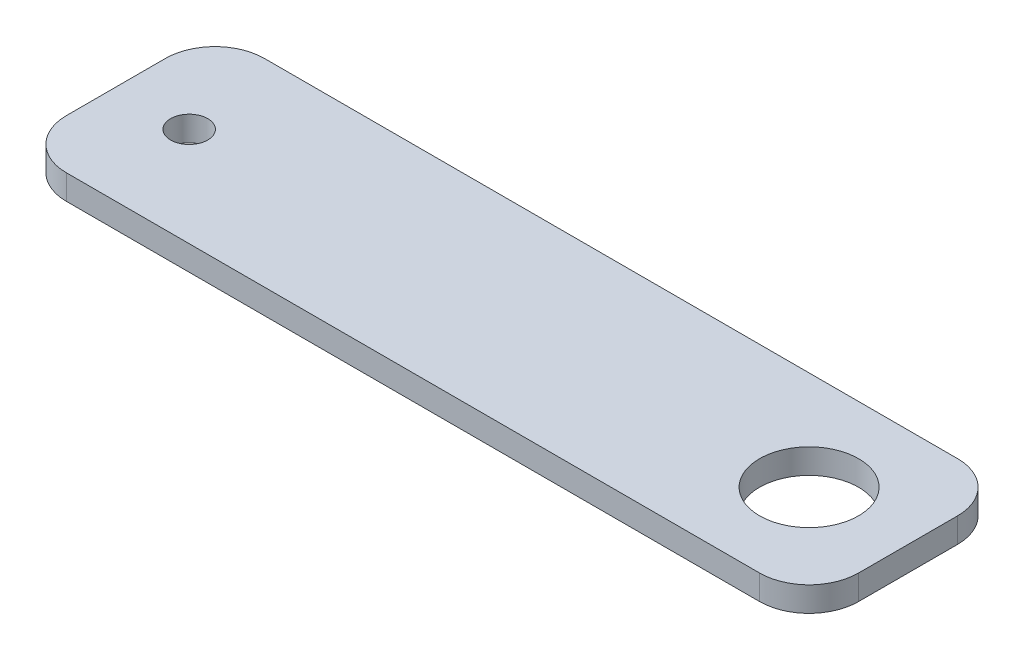
SolidWorks part; units mm, degrees
ref_plane "Front Plane" through (0, 0, 0) normal (0, 0, 1) x (1, 0, 0)
ref_plane "Top Plane" through (0, 0, 0) normal (0, 1, 0) x (1, 0, 0)
ref_plane "Right Plane" through (0, 0, 0) normal (1, 0, 0) x (0, 0, -1)
sketch "Sketch1" plane through (0, 0, 0) normal (0, 1, 0) x (1, 0, 0)
  line L1 (0, 0) -> (50.8, 0)
  line L2 (0, 0) -> (0, 12.7)
  line L3 (0, 12.7) -> (50.8, 12.7)
  line L4 (50.8, 0) -> (50.8, 12.7)
  line L5 (0, 0) -> (50.8, 12.7) construction
  line L6 (0, 12.7) -> (50.8, 0) construction
  point P4 (25.4, 6.35)
  dimension "D1" = 50.8
  dimension "D2" = 12.7
extrude "Boss-Extrude1" add sketch "Sketch1" along normal blind 1.5875
sketch "Sketch2" plane through (0, 1.5875, 0) normal (0, 1, 0) x (1, 0, 0)
  line L0 (0, 12.7) -> (0, 0) construction
  line L1 (50.8, 0) -> (50.8, 12.7) construction
  line L2 (0, 6.35) -> (50.8, 6.35) construction
  circle A0 centre (4.699, 6.35) radius 1.1906
  circle A1 centre (44.45, 6.35) radius 3.175
  point P4 (44.45, 6.35)
  point P11 (4.7663, 4.0373)
  point P12 (0, 0)
  point P13 (4.699, 6.35)
  dimension "D1" = 6.35
  dimension "D2" = 2.3813
  dimension "D4" = 6.35
  dimension "D5" = 39.751
extrude "Cut-Extrude1" cut sketch "Sketch2" against normal through all
fillet "Fillet1" radius 3.175 4 edges at (0, 0.7937, 0) (0, 0.7937, -12.7) (50.8, 0.7937, 0) (50.8, 0.7937, -12.7)
